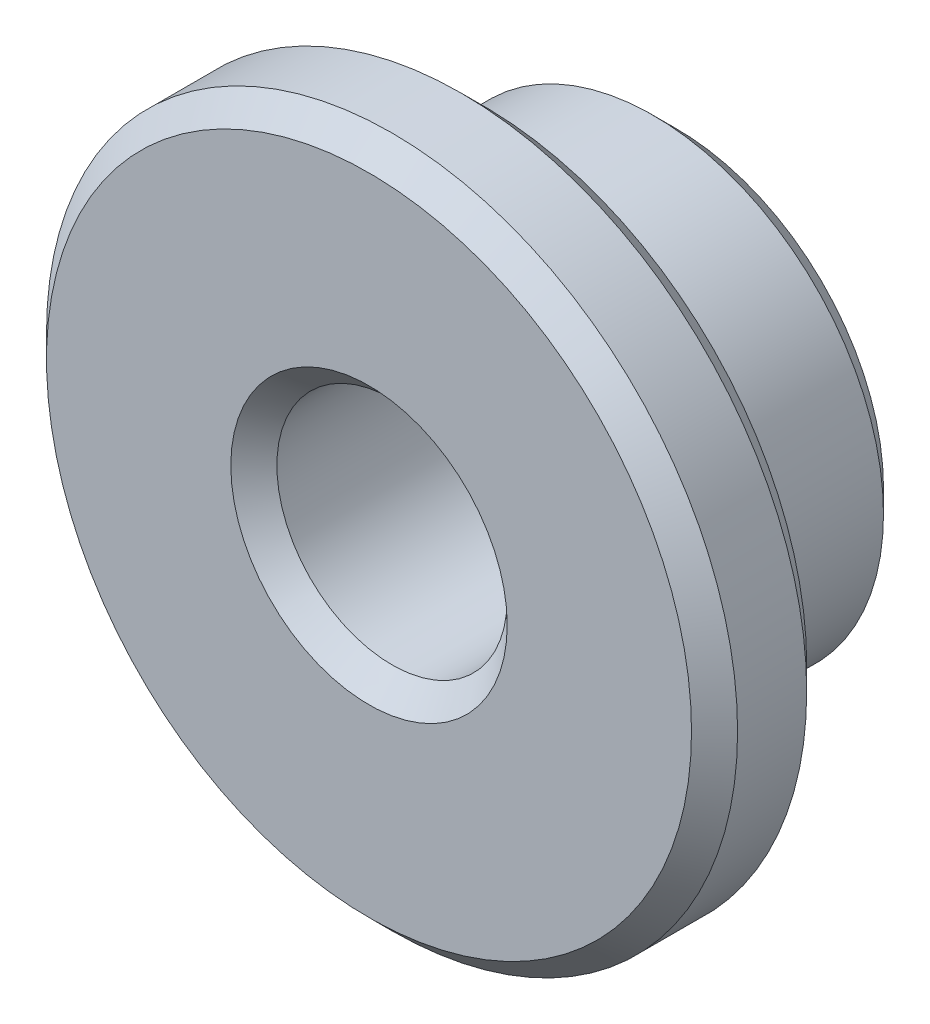
SolidWorks part; units mm, degrees
ref_plane "Přední rovina" through (0, 0, 0) normal (0, 0, 1) x (1, 0, 0)
ref_plane "Vrchní rovina" through (0, 0, 0) normal (0, 1, 0) x (1, 0, 0)
ref_plane "Pravá rovina" through (0, 0, 0) normal (1, 0, 0) x (0, 0, -1)
sketch "Skica1" plane through (0, 0, 0) normal (0, 0, 1) x (1, 0, 0)
  circle A0 centre (0, 0) radius 1.5
  circle A1 centre (0, 0) radius 3
  dimension "D1" = 3
  dimension "D2" = 6
extrude "Vysunout1" add sketch "Skica1" along normal blind 4
sketch "Skica2" plane through (0, 0, 4) normal (0, 0, 1) x (1, 0, 0)
  circle A0 centre (0, 0) radius 4.5
  circle A1 centre (0, 0) radius 3 construction
  circle A2 centre (0, 0) radius 3
  dimension "D3" = 9
extrude "Vysunout2" add sketch "Skica2" against normal blind 1.5
fillet "Zaoblit1" radius 0.45 1 edges at (3, 0, 2.5)
chamfer "Zkosit1" distance 0.3 angle 45 5 edges at (4.5, 0, 2.5) (4.5, 0, 4) (3, 0, 0) (1.5, 0, 0) (1.5, 0, 4)
equation "\"D1@Zaoblit1\" = \"SF@Vysunout2\" * 0.3"
